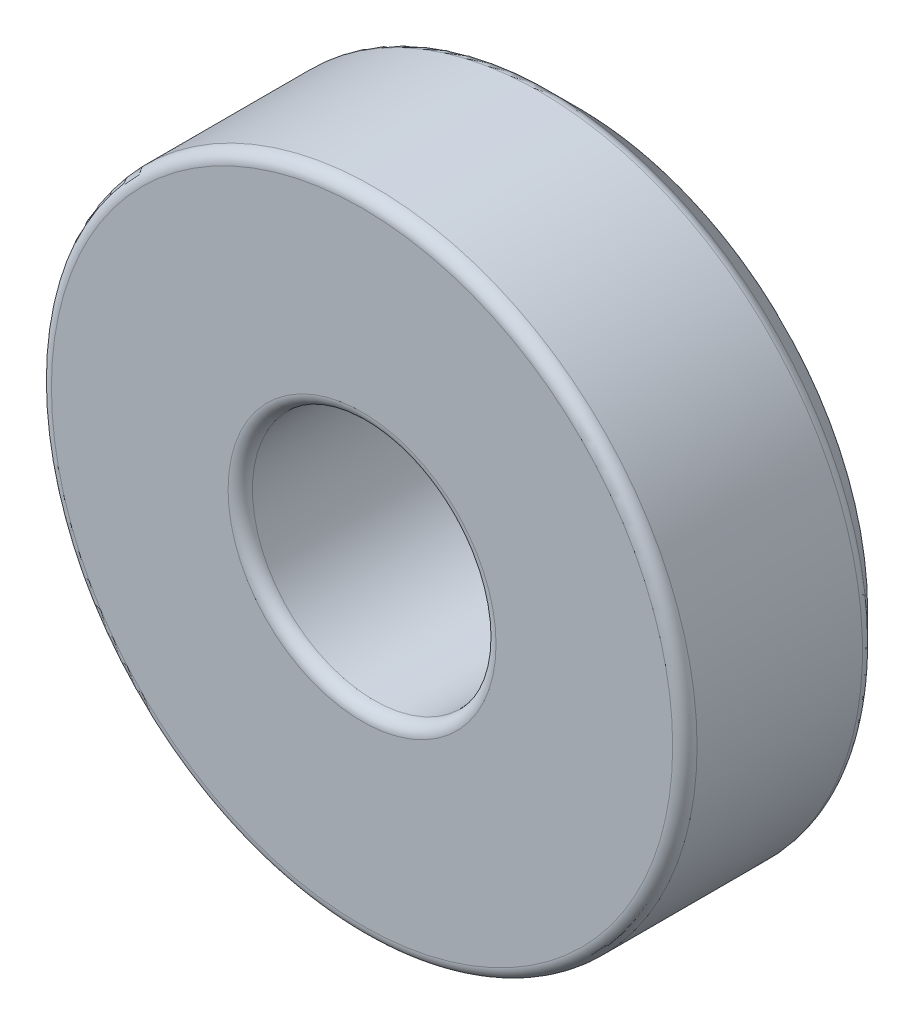
SolidWorks part; units mm, degrees
ref_plane "Front Plane" through (0, 0, 0) normal (0, 0, 1) x (1, 0, 0)
ref_plane "Top Plane" through (0, 0, 0) normal (0, 1, 0) x (1, 0, 0)
ref_plane "Right Plane" through (0, 0, 0) normal (1, 0, 0) x (0, 0, -1)
sketch "Sketch1" plane through (0, 0, 0) normal (0, 0, 1) x (1, 0, 0)
  circle A0 centre (0, 0) radius 0.5
  circle A1 centre (0, 0) radius 1.325
  dimension "D1" = 1
  dimension "D2" = 2.65
extrude "Boss-Extrude1" add sketch "Sketch1" along normal blind 0.9
chamfer "Chamfer1" distance 0.15 angle 45 1 edges at (1.325, 0, 0)
fillet "Fillet1" radius 0.05 5 edges at (1.325, 0, 0.15) (0.5, 0, 0) (1.175, 0, 0) (0.5, 0, 0.9) (1.325, 0, 0.9)
